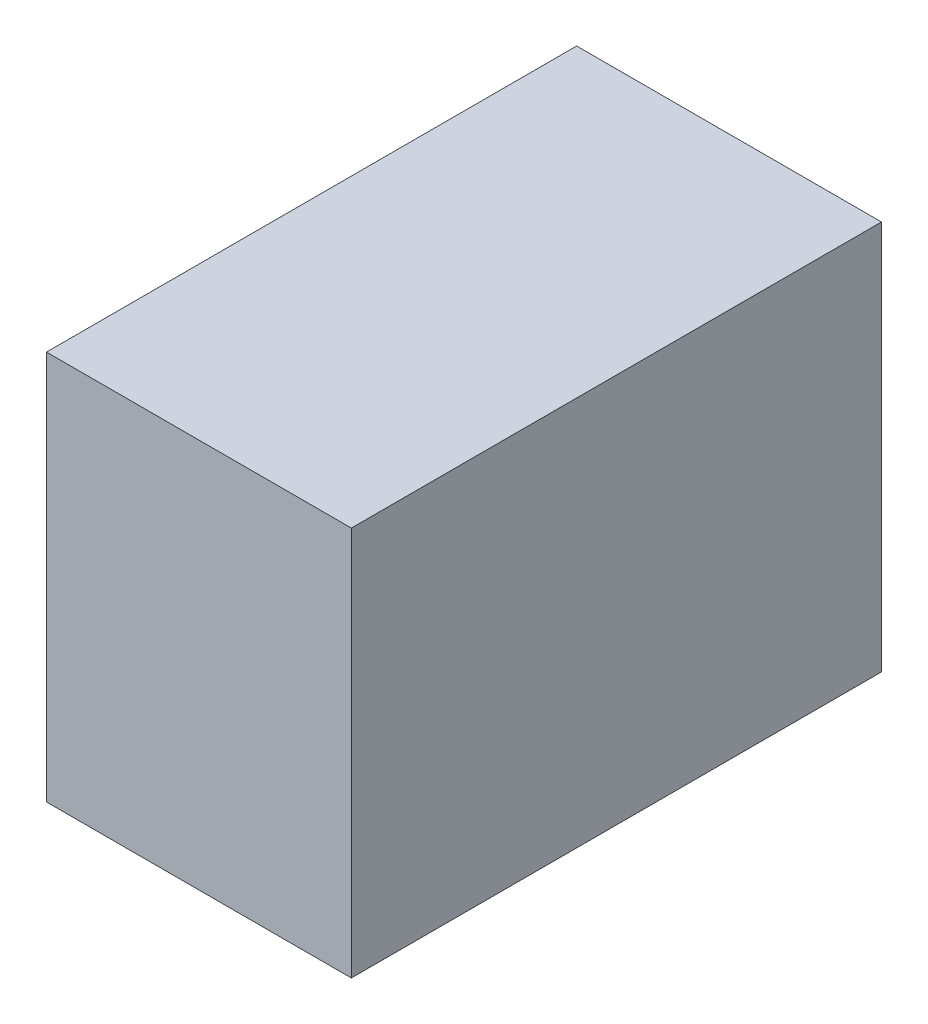
SolidWorks part; units mm, degrees
ref_plane "Front Plane" through (0, 0, 0) normal (0, 0, 1) x (1, 0, 0)
ref_plane "Top Plane" through (0, 0, 0) normal (0, 1, 0) x (1, 0, 0)
ref_plane "Right Plane" through (0, 0, 0) normal (1, 0, 0) x (0, 0, -1)
sketch "Sketch2" plane through (0, 0, 0) normal (0, 0, 1) x (1, 0, 0)
  line L1 (-2.875, 3.675) -> (2.875, 3.675)
  line L2 (-2.875, 3.675) -> (-2.875, -3.675)
  line L3 (-2.875, -3.675) -> (2.875, -3.675)
  line L4 (2.875, 3.675) -> (2.875, -3.675)
  line L5 (-2.875, 3.675) -> (2.875, -3.675) construction
  line L6 (-2.875, -3.675) -> (2.875, 3.675) construction
  point P0 (0, 0)
  dimension "D1" = 5.75
  dimension "D2" = 7.35
extrude "Boss-Extrude1" add sketch "Sketch2" along normal blind 10
